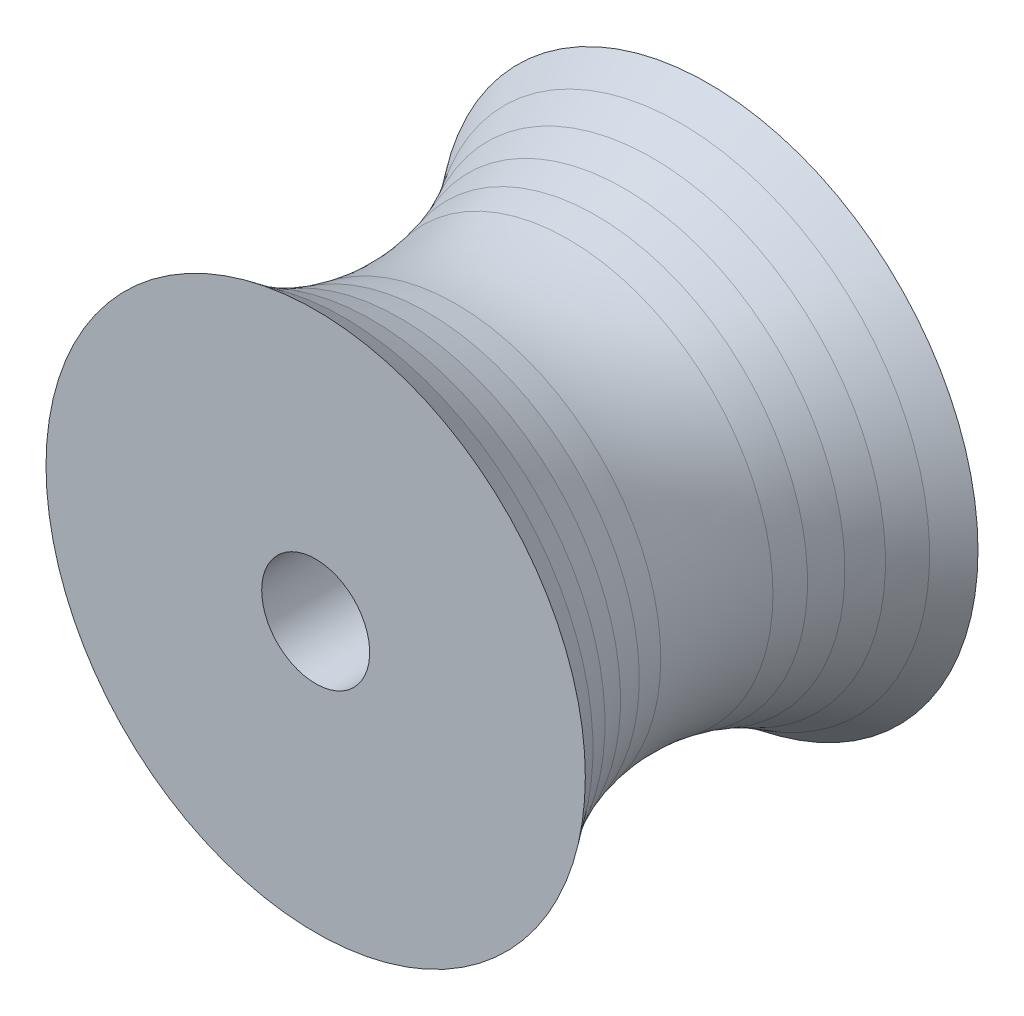
SolidWorks part; units mm, degrees
material "PE High Density"
ref_plane "Front Plane" through (0, 0, 0) normal (0, 0, 1) x (1, 0, 0)
ref_plane "Top Plane" through (0, 0, 0) normal (0, 1, 0) x (1, 0, 0)
ref_plane "Right Plane" through (0, 0, 0) normal (1, 0, 0) x (0, 0, -1)
sketch "Revolve profile 1" plane through (0, 0, 0) normal (0, 1, 0) x (1, 0, 0)
  line L0 (5.5, -20) -> (5.5, 20)
  line L1 (5.5, 20) -> (27.47, 20)
  line L2 (27.47, 20) -> (25.3946, 17.1429)
  line L3 (25.3946, 17.1429) -> (23.7575, 14.2857)
  line L4 (23.7575, 14.2857) -> (22.4854, 11.4286)
  line L5 (22.4854, 11.4286) -> (21.5328, 8.5714)
  line L6 (21.5328, 8.5714) -> (20.8701, 5.7143)
  line L7 (20.8701, -5.7143) -> (21.5328, -8.5714)
  line L8 (21.5328, -8.5714) -> (22.4854, -11.4286)
  line L9 (22.4854, -11.4286) -> (23.7575, -14.2857)
  line L10 (23.7575, -14.2857) -> (25.3946, -17.1429)
  line L11 (25.3946, -17.1429) -> (27.47, -20)
  line L12 (27.47, -20) -> (5.5, -20)
  line L13 (0, 25) -> (0, -25) construction
  arc A0 (20.8701, 5.7143) -> (20.8701, -5.7143) centre (52, 0) ccw
  dimension "D1" = 31.65
  dimension "D2" = 5.5
  dimension "D3" = 20.8701
  dimension "D4" = 21.5328
  dimension "D5" = 22.4854
  dimension "D6" = 23.7575
  dimension "D7" = 25.3946
  dimension "D8" = 27.47
  dimension "D9" = 52
revolve "Revolve 1" add sketch "Revolve profile 1" angle 360 about L13
